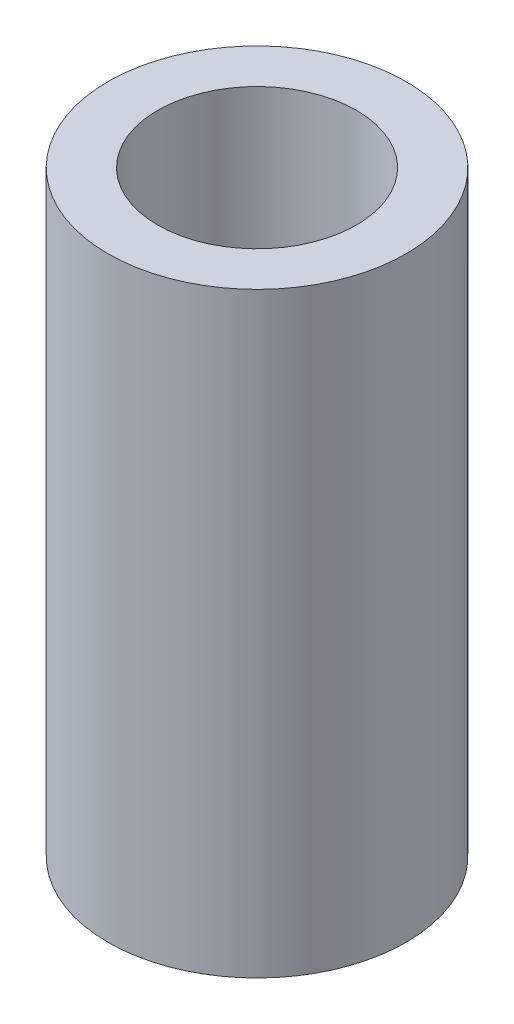
SolidWorks part; units mm, degrees
material "IGLIDUR G"
ref_plane "Front Plane" through (0, 0, 0) normal (0, 0, 1) x (1, 0, 0)
ref_plane "Top Plane" through (0, 0, 0) normal (0, 1, 0) x (1, 0, 0)
ref_plane "Right Plane" through (0, 0, 0) normal (1, 0, 0) x (0, 0, -1)
sketch "Sketch1" plane through (0, 0, 0) normal (0, 1, 0) x (1, 0, 0)
  circle A0 centre (0, 0) radius 1.5
  circle A1 centre (0, 0) radius 2.25
  dimension "D1" = 3
  dimension "D2" = 4.5
extrude "Boss-Extrude1" add sketch "Sketch1" along normal blind 9
